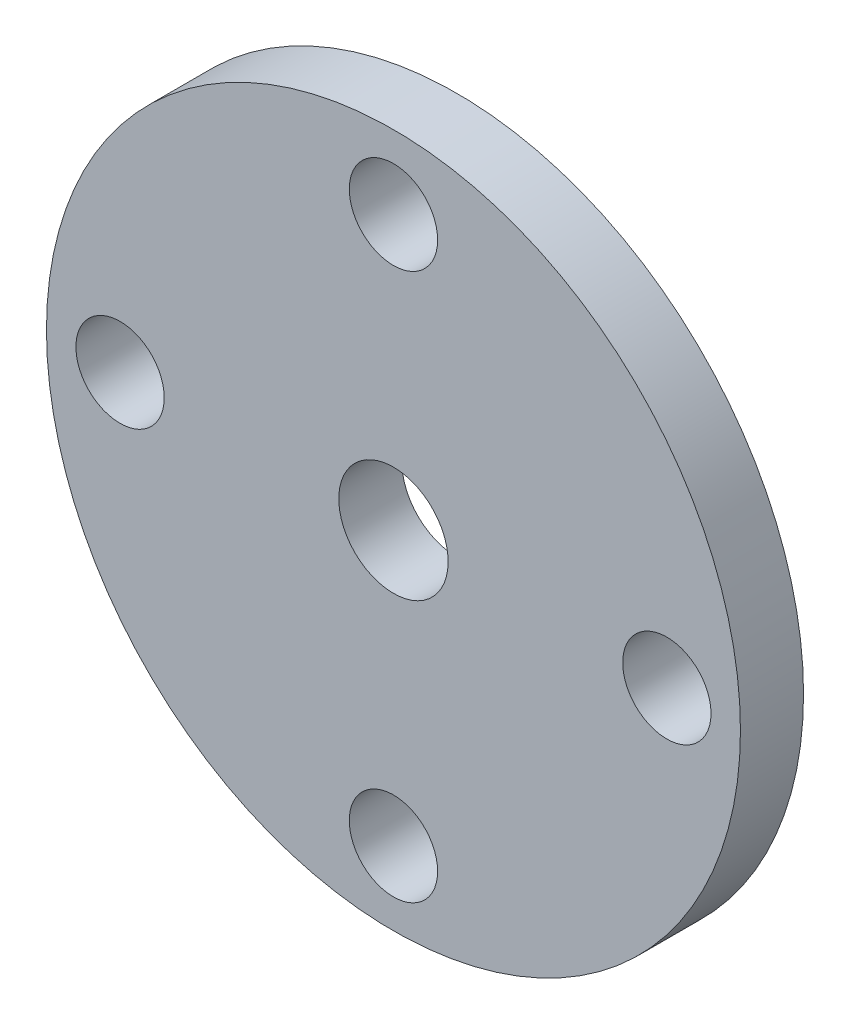
SolidWorks part; units mm, degrees
ref_plane "前视基准面" through (0, 0, 0) normal (0, 0, 1) x (1, 0, 0)
ref_plane "上视基准面" through (0, 0, 0) normal (0, 1, 0) x (1, 0, 0)
ref_plane "右视基准面" through (0, 0, 0) normal (1, 0, 0) x (0, 0, -1)
sketch "草图1" plane through (0, 0, 0) normal (0, 0, 1) x (1, 0, 0)
  circle A0 centre (0, 0) radius 13 construction
  circle A1 centre (0, 13) radius 2.1
  circle A2 centre (13, 0) radius 2.1
  circle A3 centre (0, -13) radius 2.1
  circle A4 centre (-13, 0) radius 2.1
  circle A5 centre (0, 0) radius 2.6
  circle A6 centre (0, 0) radius 16.5
  dimension "D1" = 26
  dimension "D2" = 4.2
  dimension "D4" = 5.2
  dimension "D5" = 33
  dimension "D3" = 4
extrude "凸台-拉伸1" add sketch "草图1" along normal blind 3
